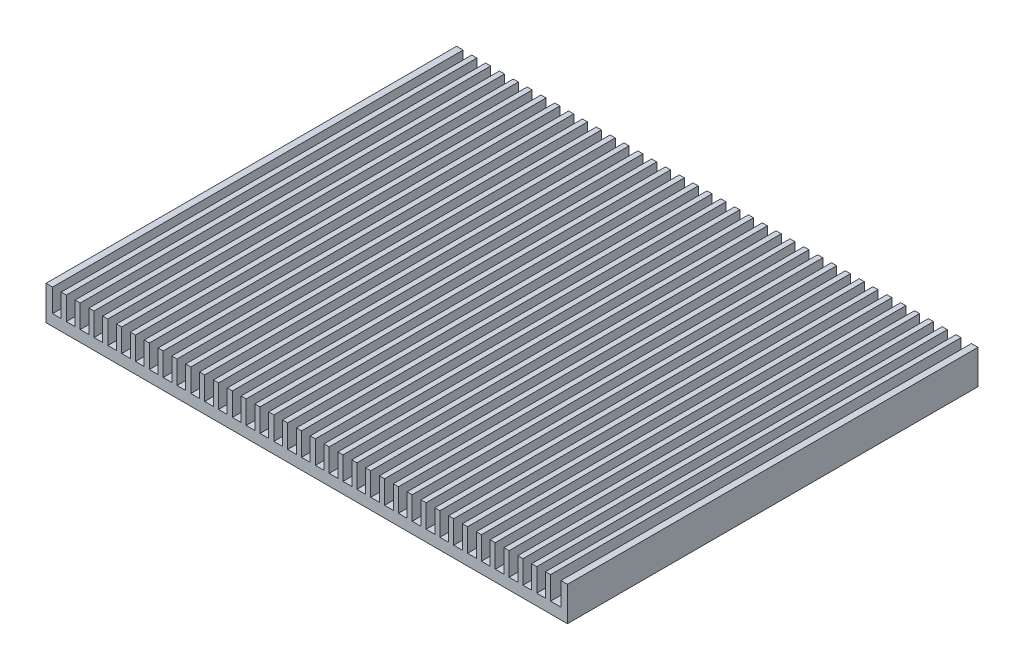
SolidWorks part; units mm, degrees
ref_plane "前视基准面" through (0, 0, 0) normal (0, 0, 1) x (1, 0, 0)
ref_plane "上视基准面" through (0, 0, 0) normal (0, 1, 0) x (1, 0, 0)
ref_plane "右视基准面" through (0, 0, 0) normal (1, 0, 0) x (0, 0, -1)
sketch "草图1" plane through (0, 0, 0) normal (0, 0, 1) x (1, 0, 0)
  line L1 (-63.5, -0.9992) -> (63.5, -0.9992)
  line L2 (-63.5, -0.9992) -> (-63.5, 1.7108)
  line L3 (-63.5, 1.7108) -> (63.5, 1.7108)
  line L4 (63.5, -0.9992) -> (63.5, 1.7108)
  line L5 (-63.5, -0.9992) -> (63.5, 1.7108) construction
  line L6 (-63.5, 1.7108) -> (63.5, -0.9992) construction
  line L7 (-63.5, 1.7108) -> (-61.9, 1.7108)
  line L8 (-63.5, 1.7108) -> (-63.5, 7.3108)
  line L9 (-63.5, 7.3108) -> (-61.9, 7.3108)
  line L10 (-61.9, 1.7108) -> (-61.9, 7.3108)
  line L11 (63.5, 1.7108) -> (61.9, 1.7108)
  line L12 (63.5, 1.7108) -> (63.5, 7.3108)
  line L13 (63.5, 7.3108) -> (61.9, 7.3108)
  line L14 (61.9, 1.7108) -> (61.9, 7.3108)
  line L15 (-59.8, 1.7108) -> (-58.55, 1.7108)
  line L16 (-59.8, 1.7108) -> (-59.8, 7.3108)
  line L17 (-59.8, 7.3108) -> (-58.55, 7.3108)
  line L18 (-58.55, 1.7108) -> (-58.55, 7.3108)
  line L19 (-56.43, 1.7108) -> (-55.18, 1.7108)
  line L20 (-56.43, 1.7108) -> (-56.43, 7.3108)
  line L21 (-56.43, 7.3108) -> (-55.18, 7.3108)
  line L22 (-55.18, 1.7108) -> (-55.18, 7.3108)
  line L23 (-53.06, 1.7108) -> (-51.81, 1.7108)
  line L24 (-53.06, 1.7108) -> (-53.06, 7.3108)
  line L25 (-53.06, 7.3108) -> (-51.81, 7.3108)
  line L26 (-51.81, 1.7108) -> (-51.81, 7.3108)
  line L27 (-49.69, 1.7108) -> (-48.44, 1.7108)
  line L28 (-49.69, 1.7108) -> (-49.69, 7.3108)
  line L29 (-49.69, 7.3108) -> (-48.44, 7.3108)
  line L30 (-48.44, 1.7108) -> (-48.44, 7.3108)
  line L31 (-46.32, 1.7108) -> (-45.07, 1.7108)
  line L32 (-46.32, 1.7108) -> (-46.32, 7.3108)
  line L33 (-46.32, 7.3108) -> (-45.07, 7.3108)
  line L34 (-45.07, 1.7108) -> (-45.07, 7.3108)
  line L35 (-42.95, 1.7108) -> (-41.7, 1.7108)
  line L36 (-42.95, 1.7108) -> (-42.95, 7.3108)
  line L37 (-42.95, 7.3108) -> (-41.7, 7.3108)
  line L38 (-41.7, 1.7108) -> (-41.7, 7.3108)
  line L39 (-39.58, 1.7108) -> (-38.33, 1.7108)
  line L40 (-39.58, 1.7108) -> (-39.58, 7.3108)
  line L41 (-39.58, 7.3108) -> (-38.33, 7.3108)
  line L42 (-38.33, 1.7108) -> (-38.33, 7.3108)
  line L43 (-36.21, 1.7108) -> (-34.96, 1.7108)
  line L44 (-36.21, 1.7108) -> (-36.21, 7.3108)
  line L45 (-36.21, 7.3108) -> (-34.96, 7.3108)
  line L46 (-34.96, 1.7108) -> (-34.96, 7.3108)
  line L47 (-32.84, 1.7108) -> (-31.59, 1.7108)
  line L48 (-32.84, 1.7108) -> (-32.84, 7.3108)
  line L49 (-32.84, 7.3108) -> (-31.59, 7.3108)
  line L50 (-31.59, 1.7108) -> (-31.59, 7.3108)
  line L51 (-29.47, 1.7108) -> (-28.22, 1.7108)
  line L52 (-29.47, 1.7108) -> (-29.47, 7.3108)
  line L53 (-29.47, 7.3108) -> (-28.22, 7.3108)
  line L54 (-28.22, 1.7108) -> (-28.22, 7.3108)
  line L55 (-26.1, 1.7108) -> (-24.85, 1.7108)
  line L56 (-26.1, 1.7108) -> (-26.1, 7.3108)
  line L57 (-26.1, 7.3108) -> (-24.85, 7.3108)
  line L58 (-24.85, 1.7108) -> (-24.85, 7.3108)
  line L59 (-22.73, 1.7108) -> (-21.48, 1.7108)
  line L60 (-22.73, 1.7108) -> (-22.73, 7.3108)
  line L61 (-22.73, 7.3108) -> (-21.48, 7.3108)
  line L62 (-21.48, 1.7108) -> (-21.48, 7.3108)
  line L63 (-19.36, 1.7108) -> (-18.11, 1.7108)
  line L64 (-19.36, 1.7108) -> (-19.36, 7.3108)
  line L65 (-19.36, 7.3108) -> (-18.11, 7.3108)
  line L66 (-18.11, 1.7108) -> (-18.11, 7.3108)
  line L67 (-15.99, 1.7108) -> (-14.74, 1.7108)
  line L68 (-15.99, 1.7108) -> (-15.99, 7.3108)
  line L69 (-15.99, 7.3108) -> (-14.74, 7.3108)
  line L70 (-14.74, 1.7108) -> (-14.74, 7.3108)
  line L71 (-12.62, 1.7108) -> (-11.37, 1.7108)
  line L72 (-12.62, 1.7108) -> (-12.62, 7.3108)
  line L73 (-12.62, 7.3108) -> (-11.37, 7.3108)
  line L74 (-11.37, 1.7108) -> (-11.37, 7.3108)
  line L75 (-9.25, 1.7108) -> (-8, 1.7108)
  line L76 (-9.25, 1.7108) -> (-9.25, 7.3108)
  line L77 (-9.25, 7.3108) -> (-8, 7.3108)
  line L78 (-8, 1.7108) -> (-8, 7.3108)
  line L79 (-5.88, 1.7108) -> (-4.63, 1.7108)
  line L80 (-5.88, 1.7108) -> (-5.88, 7.3108)
  line L81 (-5.88, 7.3108) -> (-4.63, 7.3108)
  line L82 (-4.63, 1.7108) -> (-4.63, 7.3108)
  line L83 (-2.51, 1.7108) -> (-1.26, 1.7108)
  line L84 (-2.51, 1.7108) -> (-2.51, 7.3108)
  line L85 (-2.51, 7.3108) -> (-1.26, 7.3108)
  line L86 (-1.26, 1.7108) -> (-1.26, 7.3108)
  line L87 (0.86, 1.7108) -> (2.11, 1.7108)
  line L88 (0.86, 1.7108) -> (0.86, 7.3108)
  line L89 (0.86, 7.3108) -> (2.11, 7.3108)
  line L90 (2.11, 1.7108) -> (2.11, 7.3108)
  line L91 (4.23, 1.7108) -> (5.48, 1.7108)
  line L92 (4.23, 1.7108) -> (4.23, 7.3108)
  line L93 (4.23, 7.3108) -> (5.48, 7.3108)
  line L94 (5.48, 1.7108) -> (5.48, 7.3108)
  line L95 (7.6, 1.7108) -> (8.85, 1.7108)
  line L96 (7.6, 1.7108) -> (7.6, 7.3108)
  line L97 (7.6, 7.3108) -> (8.85, 7.3108)
  line L98 (8.85, 1.7108) -> (8.85, 7.3108)
  line L99 (10.97, 1.7108) -> (12.22, 1.7108)
  line L100 (10.97, 1.7108) -> (10.97, 7.3108)
  line L101 (10.97, 7.3108) -> (12.22, 7.3108)
  line L102 (12.22, 1.7108) -> (12.22, 7.3108)
  line L103 (14.34, 1.7108) -> (15.59, 1.7108)
  line L104 (14.34, 1.7108) -> (14.34, 7.3108)
  line L105 (14.34, 7.3108) -> (15.59, 7.3108)
  line L106 (15.59, 1.7108) -> (15.59, 7.3108)
  line L107 (17.71, 1.7108) -> (18.96, 1.7108)
  line L108 (17.71, 1.7108) -> (17.71, 7.3108)
  line L109 (17.71, 7.3108) -> (18.96, 7.3108)
  line L110 (18.96, 1.7108) -> (18.96, 7.3108)
  line L111 (21.08, 1.7108) -> (22.33, 1.7108)
  line L112 (21.08, 1.7108) -> (21.08, 7.3108)
  line L113 (21.08, 7.3108) -> (22.33, 7.3108)
  line L114 (22.33, 1.7108) -> (22.33, 7.3108)
  line L115 (24.45, 1.7108) -> (25.7, 1.7108)
  line L116 (24.45, 1.7108) -> (24.45, 7.3108)
  line L117 (24.45, 7.3108) -> (25.7, 7.3108)
  line L118 (25.7, 1.7108) -> (25.7, 7.3108)
  line L119 (27.82, 1.7108) -> (29.07, 1.7108)
  line L120 (27.82, 1.7108) -> (27.82, 7.3108)
  line L121 (27.82, 7.3108) -> (29.07, 7.3108)
  line L122 (29.07, 1.7108) -> (29.07, 7.3108)
  line L123 (31.19, 1.7108) -> (32.44, 1.7108)
  line L124 (31.19, 1.7108) -> (31.19, 7.3108)
  line L125 (31.19, 7.3108) -> (32.44, 7.3108)
  line L126 (32.44, 1.7108) -> (32.44, 7.3108)
  line L127 (34.56, 1.7108) -> (35.81, 1.7108)
  line L128 (34.56, 1.7108) -> (34.56, 7.3108)
  line L129 (34.56, 7.3108) -> (35.81, 7.3108)
  line L130 (35.81, 1.7108) -> (35.81, 7.3108)
  line L131 (37.93, 1.7108) -> (39.18, 1.7108)
  line L132 (37.93, 1.7108) -> (37.93, 7.3108)
  line L133 (37.93, 7.3108) -> (39.18, 7.3108)
  line L134 (39.18, 1.7108) -> (39.18, 7.3108)
  line L135 (41.3, 1.7108) -> (42.55, 1.7108)
  line L136 (41.3, 1.7108) -> (41.3, 7.3108)
  line L137 (41.3, 7.3108) -> (42.55, 7.3108)
  line L138 (42.55, 1.7108) -> (42.55, 7.3108)
  line L139 (44.67, 1.7108) -> (45.92, 1.7108)
  line L140 (44.67, 1.7108) -> (44.67, 7.3108)
  line L141 (44.67, 7.3108) -> (45.92, 7.3108)
  line L142 (45.92, 1.7108) -> (45.92, 7.3108)
  line L143 (48.04, 1.7108) -> (49.29, 1.7108)
  line L144 (48.04, 1.7108) -> (48.04, 7.3108)
  line L145 (48.04, 7.3108) -> (49.29, 7.3108)
  line L146 (49.29, 1.7108) -> (49.29, 7.3108)
  line L147 (51.41, 1.7108) -> (52.66, 1.7108)
  line L148 (51.41, 1.7108) -> (51.41, 7.3108)
  line L149 (51.41, 7.3108) -> (52.66, 7.3108)
  line L150 (52.66, 1.7108) -> (52.66, 7.3108)
  line L151 (54.78, 1.7108) -> (56.03, 1.7108)
  line L152 (54.78, 1.7108) -> (54.78, 7.3108)
  line L153 (54.78, 7.3108) -> (56.03, 7.3108)
  line L154 (56.03, 1.7108) -> (56.03, 7.3108)
  line L155 (58.15, 1.7108) -> (59.4, 1.7108)
  line L156 (58.15, 1.7108) -> (58.15, 7.3108)
  line L157 (58.15, 7.3108) -> (59.4, 7.3108)
  line L158 (59.4, 1.7108) -> (59.4, 7.3108)
  line L159 (-59.8, 1.7108) -> (-56.43, 1.7108) construction
  dimension "D1" = 1.6
  dimension "D2" = 1.6
  dimension "D3" = 1.25
  dimension "D4" = 2.1
  dimension "D6" = 127
  dimension "D7" = 3.37
  dimension "D8" = 2.71
  dimension "D9" = 8.31
  dimension "D5" = 36
extrude "凸台-拉伸1" add sketch "草图1" along normal blind 100 contours L1 L4 L3 | L3 L90 L89 L88 | L3 L86 L85 L84 | L3 L82 L81 L80 | L3 L78 L77 L76 | L3 L74 L73 L72 | L3 L70 L69 L68 | L3 L66 L65 L64 | L3 L62 L61 L60 | L3 L58 L57 L56 | L3 L10 L9 L8 | L3 L18 L17 L16 | L3 L22 L21 L20 | L3 L30 L29 L28 | L3 L34 L33 L32 | L3 L38 L37 L36 | L3 L42 L41 L40 | L3 L46 L45 L44 | L3 L50 L49 L48 | L3 L54 L53 L52 | L14 L3 L12 L13 | L3 L154 L153 L152 | L3 L150 L149 L148 | L3 L146 L145 L144 | L3 L142 L141 L140 | L3 L138 L137 L136 | L3 L134 L133 L132 | L3 L130 L129 L128 | L3 L126 L125 L124 | L3 L122 L121 L120 | L3 L118 L117 L116 | L3 L114 L113 L112 | L3 L110 L109 L108 | L3 L106 L105 L104 | L3 L102 L101 L100 | L3 L98 L97 L96 | L3 L94 L93 L92 | L24 L25 L26 L23 | L158 L157 L156 L155
